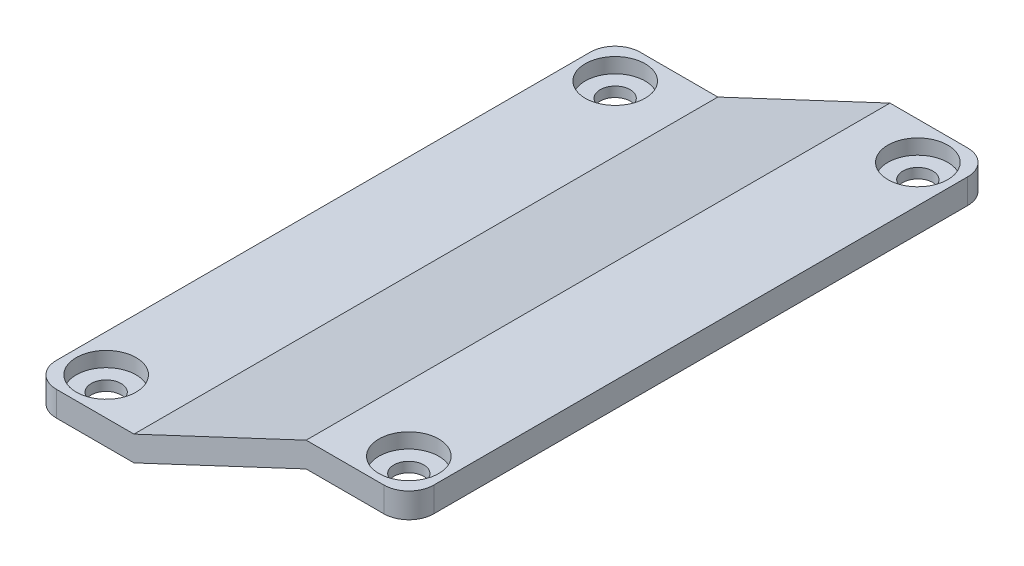
SolidWorks part; units mm, degrees
ref_plane "Front Plane" through (0, 0, 0) normal (0, 0, 1) x (1, 0, 0)
ref_plane "Top Plane" through (0, 0, 0) normal (0, 1, 0) x (1, 0, 0)
ref_plane "Right Plane" through (0, 0, 0) normal (1, 0, 0) x (0, 0, -1)
sketch "Sketch1" plane through (0, 0, 0) normal (0, 0, 1) x (1, 0, 0)
  line L0 (-17.5078, -4.569) -> (16.9922, 11.631)
  line L1 (-17.5078, -9.569) -> (-38.0828, -9.569)
  line L2 (-17.5078, -4.569) -> (-38.0828, -4.569)
  line L3 (-38.0828, -9.569) -> (-38.0828, -4.569)
  line L4 (16.9922, 6.631) -> (37.5672, 6.631)
  line L5 (16.9922, 11.631) -> (37.5672, 11.631)
  line L6 (37.5672, 6.631) -> (37.5672, 11.631)
  line L7 (-17.5078, -9.569) -> (16.9922, 6.631)
  dimension "D1" = 20.575
  dimension "D2" = 20.575
  dimension "D3" = 75.65
  dimension "D4" = 21.2
extrude "Cover Body" add sketch "Sketch1" against normal blind 117
sketch "Screw Hole outlines" plane through (0, -4.569, 0) normal (0, 1, 0) x (1, 0, 0)
  line L0 (16.9922, 117) -> (-17.5078, 117) construction
  line L1 (-30.5828, 109.5) -> (29.0672, 109.5) construction
  line L2 (-30.5828, 109.5) -> (-30.5828, 7.5) construction
  line L3 (-30.5828, 7.5) -> (29.0672, 7.5) construction
  line L4 (29.0672, 109.5) -> (29.0672, 7.5) construction
  line L5 (-38.0828, 117) -> (-38.0828, 0) construction
  line L6 (37.5672, 117) -> (37.5672, 0) construction
  line L8 (37.5672, 0) -> (16.9922, 0) construction
  dimension "D1" = 7.5
  dimension "D2" = 8.5
  dimension "D3" = 7.5
  dimension "7.5" = 7.5
hole_wizard "CBORE for M6 Hex Head Bolt1" positions "Sketch2" profile "Sketch4" counterbore size "M6" standard "ANSI Metric" end condition through all
sketch "Sketch2" plane through (0, -4.569, 0) normal (0, 1, 0) x (1, 0, 0)
  line L0 (-38.0828, 117) -> (-38.0828, 0) construction
  line L1 (-17.5078, 0) -> (-38.0828, 0) construction
  line L2 (-17.5078, 117) -> (-38.0828, 117) construction
  point P0 (-30.5828, 109.5)
  point P3 (-30.5828, 7.5)
  dimension "D1" = 7.5
  dimension "D2" = 7.5
  dimension "D3" = 7.5
  dimension "D4" = 7.5
sketch "Sketch4" plane through (-30.5828, -4.569, -109.5) normal (1, 0, 0) x (0, 0, 1)
  line L0 (0, 0) -> (0, 5)
  line L1 (0, 5) -> (3, 5)
  line L3 (3, 5) -> (3, 3)
  line L4 (3, 3) -> (6, 3)
  line L5 (6, 3) -> (6, 0)
  line L7 (6, 0) -> (0, 0)
  line L11 (0, -6.35) -> (0, 107.95) construction
  dimension "Thru Hole Dia." = 6
  dimension "Thru Hole Depth" = 5
  dimension "C'Bore Dia." = 12
  dimension "C'Bore Depth" = 3
ref_plane "Upper Lid Plane" through (29.0672, 0, 0) normal (1, 0, 0) x (0, 0, -1)
sketch "Sketch9" plane through (29.0672, 0, 0) normal (1, 0, 0) x (0, 0, -1)
  line L0 (8.5, -4.569) -> (8.5, 11.631) construction
  line L1 (109.5, -4.569) -> (7.5, -4.569) construction
  line L2 (109.5, -4.569) -> (7.5, -4.569) construction
  line L3 (117, 11.631) -> (0, 11.631) construction
  line L4 (85.5, -4.569) -> (85.5, 11.631) construction
  dimension "D1" = 77
hole_wizard "CBORE for M6 Hex Head Bolt2" positions "Sketch10" profile "Sketch11" counterbore size "M6" standard "ANSI Metric" end condition up to next
sketch "Sketch10" plane through (0, 11.631, 0) normal (0, 1, 0) x (1, 0, 0)
  line L0 (-30.5828, 109.5) -> (39.7843, 109.5) construction
  line L2 (30.0672, 115.1486) -> (30.0672, -7.1503) construction
  line L4 (37.5672, 117) -> (37.5672, 0) construction
  line L5 (37.5672, 0) -> (16.9922, 0) construction
  point P0 (30.0672, 7.5)
  point P19 (30.0672, 109.5)
  dimension "D1" = 102
  dimension "D2" = 7.5
  dimension "D3" = 7.5
sketch "Sketch11" plane through (30.0672, 11.631, -7.5) normal (1, 0, 0) x (0, 0, 1)
  line L0 (0, 0) -> (0, 5)
  line L1 (0, 5) -> (3, 5)
  line L3 (3, 5) -> (3, 3)
  line L4 (3, 3) -> (6, 3)
  line L5 (6, 3) -> (6, 0)
  line L7 (6, 0) -> (0, 0)
  line L11 (0, -6.35) -> (0, 107.95) construction
  dimension "Thru Hole Dia." = 6
  dimension "Thru Hole Depth" = 5
  dimension "C'Bore Dia." = 12
  dimension "C'Bore Depth" = 3
fillet "Fillet1" radius 5 4 edges at (-38.0828, -7.069, -117) (37.5672, 9.131, -117) (37.5672, 9.131, 0) (-38.0828, -7.069, 0)
